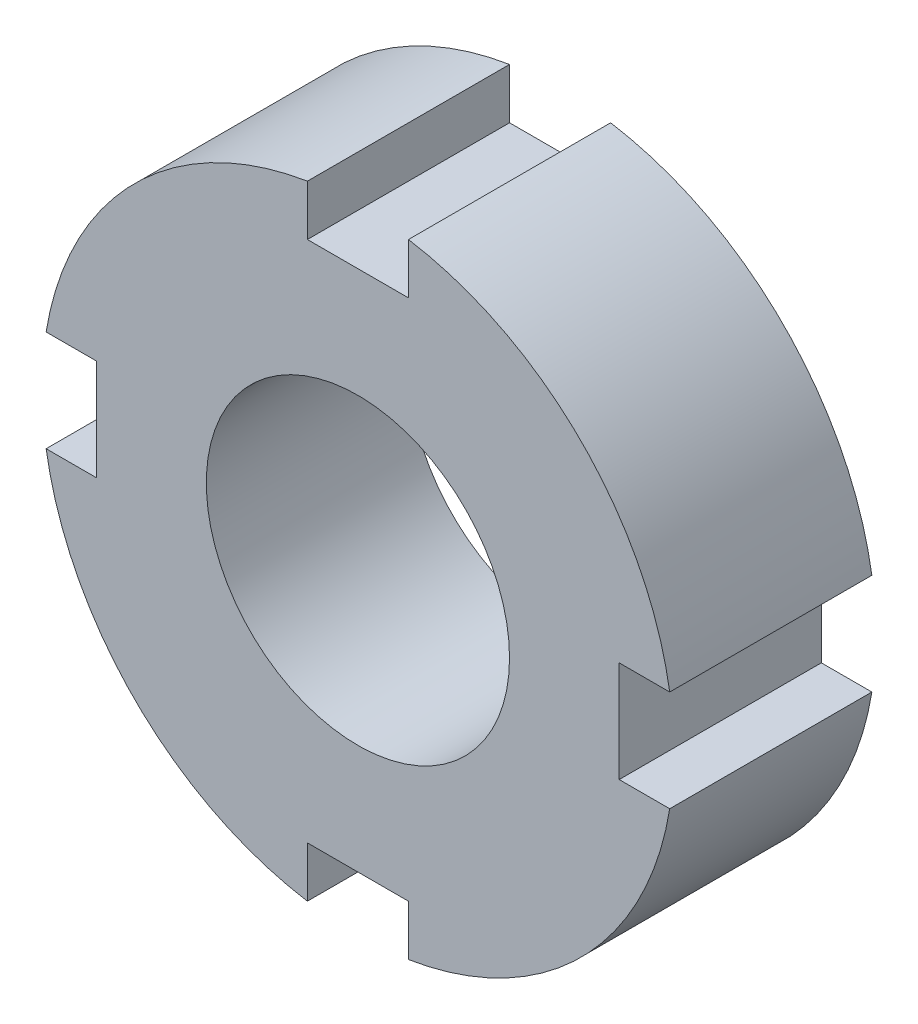
SolidWorks part; units mm, degrees
ref_plane "Plano frontal" through (0, 0, 0) normal (0, 0, 1) x (1, 0, 0)
ref_plane "Plano superior" through (0, 0, 0) normal (0, 1, 0) x (1, 0, 0)
ref_plane "Plano direito" through (0, 0, 0) normal (1, 0, 0) x (0, 0, -1)
sketch "Esboço1" plane through (0, 0, 0) normal (0, 0, 1) x (1, 0, 0)
  line L0 (-22.5788, 0) -> (20.5822, 0) construction
  line L1 (0, 13.9039) -> (0, -14.9432) construction
  line L2 (-2, 10.339) -> (2, 10.339)
  line L3 (2, 10.339) -> (2, 12.339)
  line L4 (-2, 10.339) -> (-2, 12.339)
  line L5 (10.339, 2) -> (10.339, -2)
  line L6 (10.339, -2) -> (12.339, -2)
  line L7 (10.339, 2) -> (12.339, 2)
  line L8 (2, -10.339) -> (2, -12.339)
  line L9 (-2, -10.339) -> (-2, -12.339)
  line L10 (-2, -10.339) -> (2, -10.339)
  line L11 (-10.339, -2) -> (-12.339, -2)
  line L12 (-10.339, 2) -> (-10.339, -2)
  line L13 (-10.339, 2) -> (-12.339, 2)
  circle A0 centre (0, 0) radius 12.5
  circle A1 centre (0, 0) radius 6
  point P11 (0, 10.339)
  point P16 (10.339, 0)
  dimension "D1" = 25
  dimension "D2" = 12
  dimension "D3" = 4
  dimension "D4" = 2
  dimension "D5" = 4
  dimension "D6" = 2
extrude "Ressalto-extrusão1" add sketch "Esboço1" along normal blind 8 contours L7 A0 L3 L2 L4 L13 L12 L11 L9 L10 L8 L6 L5 A1
